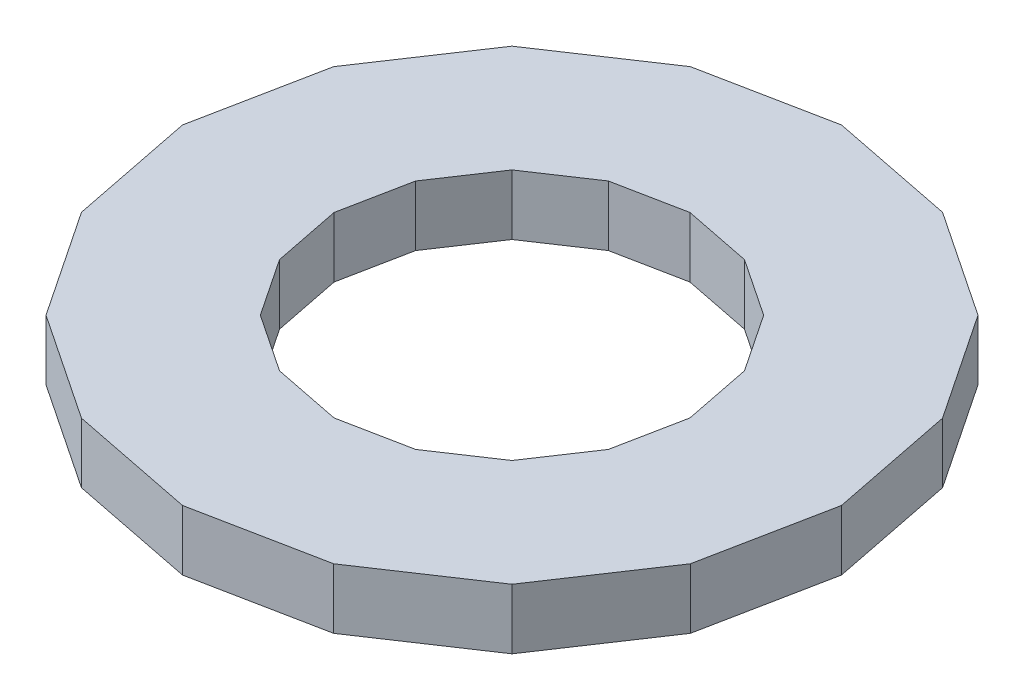
SolidWorks part; units mm, degrees
ref_plane "Front Plane" through (0, 0, 0) normal (0, 0, 1) x (1, 0, 0)
ref_plane "Top Plane" through (0, 0, 0) normal (0, 1, 0) x (1, 0, 0)
ref_plane "Right Plane" through (0, 0, 0) normal (1, 0, 0) x (0, 0, -1)
sketch "Sketch1" plane through (0, 0, 0) normal (0, 1, 0) x (1, 0, 0)
  line L1 (56.2463, 0) -> (51.9648, 21.5245)
  line L2 (51.9648, 21.5245) -> (39.7721, 39.7721)
  line L3 (39.7721, 39.7721) -> (21.5245, 51.9648)
  line L4 (21.5245, 51.9648) -> (0, 56.2463)
  line L5 (0, 56.2463) -> (-21.5245, 51.9648)
  line L6 (-21.5245, 51.9648) -> (-39.7721, 39.7721)
  line L7 (-39.7721, 39.7721) -> (-51.9648, 21.5245)
  line L8 (-51.9648, 21.5245) -> (-56.2463, 0)
  line L9 (-56.2463, 0) -> (-51.9648, -21.5245)
  line L10 (-51.9648, -21.5245) -> (-39.7721, -39.7721)
  line L11 (-39.7721, -39.7721) -> (-21.5245, -51.9648)
  line L12 (-21.5245, -51.9648) -> (0, -56.2463)
  line L13 (0, -56.2463) -> (21.5245, -51.9648)
  line L14 (21.5245, -51.9648) -> (39.7721, -39.7721)
  line L15 (39.7721, -39.7721) -> (51.9648, -21.5245)
  line L16 (51.9648, -21.5245) -> (56.2463, 0)
  line L17 (104.1569, 0) -> (96.2284, 39.8591)
  line L18 (96.2284, 39.8591) -> (73.65, 73.65)
  line L19 (73.65, 73.65) -> (39.8591, 96.2284)
  line L20 (39.8591, 96.2284) -> (0, 104.1569)
  line L21 (0, 104.1569) -> (-39.8591, 96.2284)
  line L22 (-39.8591, 96.2284) -> (-73.65, 73.65)
  line L23 (-73.65, 73.65) -> (-96.2284, 39.8591)
  line L24 (-96.2284, 39.8591) -> (-104.1569, 0)
  line L25 (-104.1569, 0) -> (-96.2284, -39.8591)
  line L26 (-96.2284, -39.8591) -> (-73.65, -73.65)
  line L27 (-73.65, -73.65) -> (-39.8591, -96.2284)
  line L28 (-39.8591, -96.2284) -> (0, -104.1569)
  line L29 (0, -104.1569) -> (39.8591, -96.2284)
  line L30 (39.8591, -96.2284) -> (73.65, -73.65)
  line L31 (73.65, -73.65) -> (96.2284, -39.8591)
  line L32 (96.2284, -39.8591) -> (104.1569, 0)
  circle A1 centre (0, 0) radius 55.1655 construction
  circle A2 centre (0, 0) radius 102.1555 construction
  dimension "D1" = 46.99
  dimension "D2" = 40.64
extrude "Boss-Extrude1" add sketch "Sketch1" along normal blind 19.05
